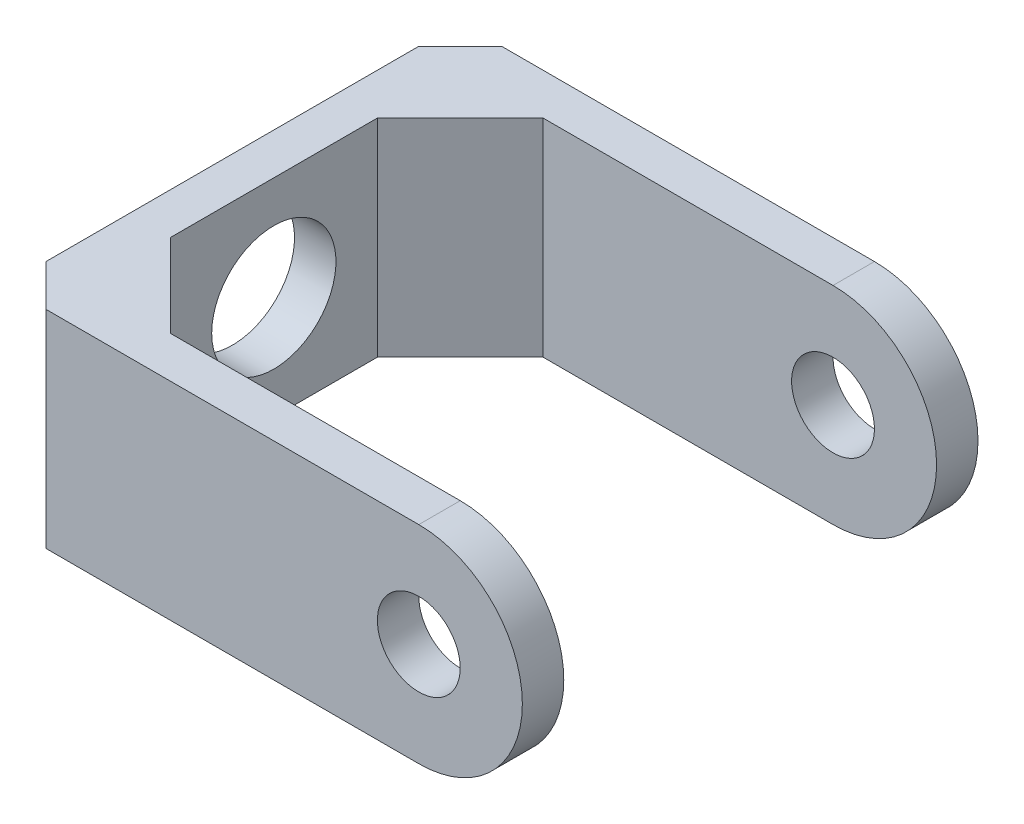
SolidWorks part; units mm, degrees
ref_plane "前视基准面" through (0, 0, 0) normal (0, 0, 1) x (1, 0, 0)
ref_plane "上视基准面" through (0, 0, 0) normal (0, 1, 0) x (1, 0, 0)
ref_plane "右视基准面" through (0, 0, 0) normal (1, 0, 0) x (0, 0, -1)
other "Configuration Table"
sketch "草图1" plane through (0, 0, 0) normal (0, 0, 1) x (1, 0, 0)
  line L1 (0, 0) -> (18, 0)
  line L2 (0, 0) -> (0, 10)
  line L3 (0, 10) -> (18, 10)
  arc A0 (18, 0) -> (18, 10) centre (18, 5) ccw
  circle A1 centre (18, 5) radius 2
  dimension "D3" = 4
  dimension "D1" = 18
  dimension "D2" = 10
extrude "凸台-拉伸1" add sketch "草图1" along normal blind 2
ref_plane "基准面2" through (0, 0, 11) normal (0, 0, 1) x (1, 0, 0)
mirror "镜向1" about plane through (0, 0, 11) normal (0, 0, 1) of bodies 106
sketch "草图6" plane through (0, 0, 0) normal (-1, 0, 0) x (0, 0, 1)
  line L1 (0, 10) -> (22, 10)
  line L2 (0, 10) -> (0, 0)
  line L3 (0, 0) -> (22, 0)
  line L4 (22, 10) -> (22, 0)
  dimension "D1" = 22
extrude "凸台-拉伸5" add sketch "草图6" along normal blind 2
chamfer "倒角2" distance 2 angle 45 2 edges at (-2, 5, 22) (-2, 5, 0)
chamfer "倒角3" distance 4 angle 45 2 edges at (0, 5, 20) (0, 5, 2)
sketch "草图7" plane through (-2, 0, 0) normal (-1, 0, 0) x (0, 0, 1)
  line L0 (2, 10) -> (20, 0) construction
  circle A0 centre (11, 5) radius 3
  dimension "D1" = 6
extrude "切除-拉伸2" cut sketch "草图7" against normal through all
ref_plane "基准面1" through (0, 5, 0) normal (0, 1, 0) x (1, 0, 0)
